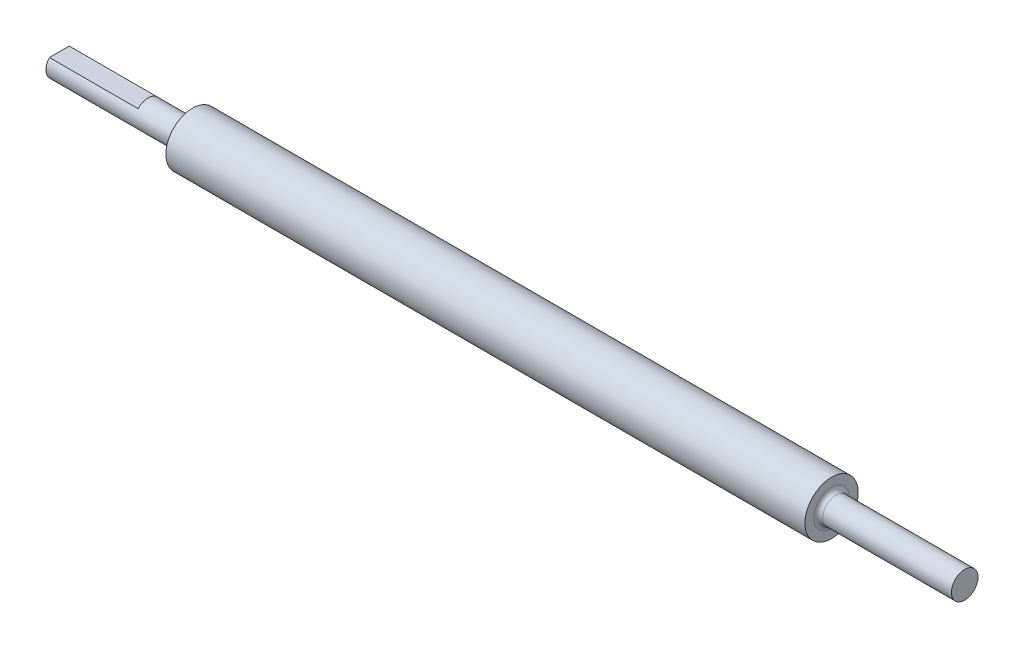
SolidWorks part; units mm, degrees
ref_plane "Front Plane" through (0, 0, 0) normal (0, 0, 1) x (1, 0, 0)
ref_plane "Top Plane" through (0, 0, 0) normal (0, 1, 0) x (1, 0, 0)
ref_plane "Right Plane" through (0, 0, 0) normal (1, 0, 0) x (0, 0, -1)
sketch "Sketch1" plane through (0, 0, 0) normal (0, 1, 0) x (1, 0, 0)
  line L0 (-29.559, -16.4809) -> (72.441, -16.4809)
  line L1 (-14.559, -13.4809) -> (57.441, -13.4809)
  line L2 (-29.559, -16.4809) -> (-29.559, -14.9809)
  line L3 (-29.559, -14.9809) -> (-14.559, -14.9809)
  line L4 (-14.559, -13.4809) -> (-14.559, -14.9809)
  line L5 (57.441, -14.9809) -> (72.441, -14.9809)
  line L6 (72.441, -14.9809) -> (72.441, -16.4809)
  line L7 (57.441, -13.4809) -> (57.441, -14.9809)
  dimension "D1" = 72
  dimension "D2" = 3
  dimension "D3" = 1.5
  dimension "D4" = 15
  dimension "D5" = 15
revolve "Revolve1" add sketch "Sketch1" angle 360 about L0
fillet "Fillet1" radius 0.5 2 edges at (57.441, 0, 17.9809) (-14.559, 0, 17.9809)
sketch "Sketch2" plane through (-29.559, 0, 0) normal (-1, 0, 0) x (0, 0, 1)
  line L0 (15.3629, 1) -> (17.599, 1)
  circle A0 centre (16.4809, 0) radius 1.5 construction
  arc A1 (15.3629, 1) -> (17.599, 1) centre (16.4809, 0) cw
  dimension "D1" = 1
extrude "Cut-Extrude1" cut sketch "Sketch2" against normal blind 10
